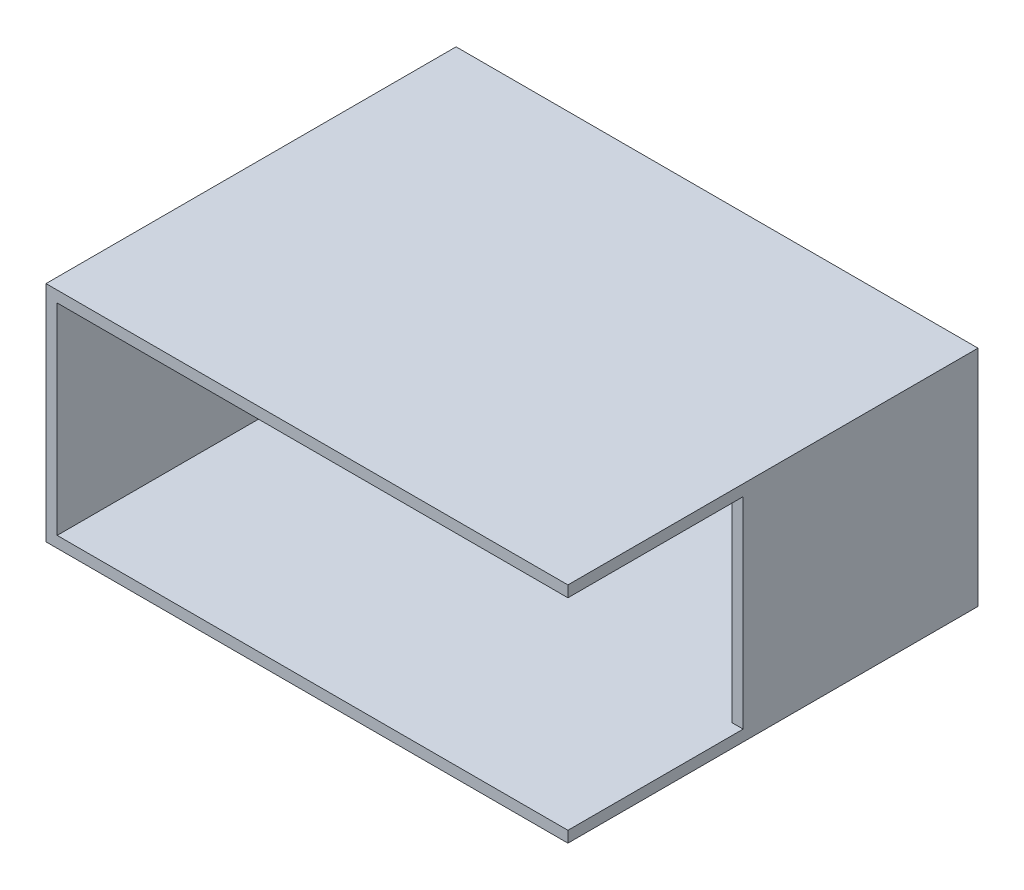
SolidWorks part; units mm, degrees
ref_plane "Front Plane" through (0, 0, 0) normal (1, 0, 0) x (0, 1, 0)
ref_plane "Top Plane" through (0, 0, 0) normal (0, 0, 1) x (0, 1, 0)
ref_plane "Right Plane" through (0, 0, 0) normal (0, 1, 0) x (-1, 0, 0)
sketch "Sketch1" plane through (0, 0, 0) normal (1, 0, 0) x (0, 1, 0)
  line L1 (0, 0) -> (76.2, 0)
  line L2 (0, 0) -> (0, 139.7)
  line L3 (0, 139.7) -> (76.2, 139.7)
  line L4 (76.2, 0) -> (76.2, 139.7)
  dimension "D1" = 139.7
  dimension "D2" = 76.2
extrude "Boss-Extrude1" add sketch "Sketch1" along normal blind 177.8
sketch "Sketch2" plane through (177.8, 0, 0) normal (1, 0, 0) x (0, 1, 0)
  line L0 (76.2, 139.7) -> (0, 139.7) construction
  line L1 (3.81, 139.7) -> (72.39, 139.7)
  line L2 (3.81, 139.7) -> (3.81, 3.81)
  line L3 (3.81, 3.81) -> (72.39, 3.81)
  line L4 (72.39, 139.7) -> (72.39, 3.81)
  line L5 (0, 139.7) -> (0, 0) construction
  line L6 (0, 0) -> (76.2, 0) construction
  line L7 (76.2, 0) -> (76.2, 139.7) construction
  dimension "D1" = 3.81
  dimension "D2" = 3.81
  dimension "D3" = 3.81
extrude "Cut-Extrude1" cut sketch "Sketch2" against normal blind 173.99
sketch "Sketch3" plane through (0, 0, 3.81) normal (0, 0, 1) x (1, 0, 0)
  line L0 (3.81, 3.81) -> (177.8, 3.81) construction
  line L1 (24.13, 29.21) -> (168.91, 29.21)
  line L2 (24.13, 29.21) -> (24.13, 46.99)
  line L3 (24.13, 46.99) -> (168.91, 46.99)
  line L4 (168.91, 29.21) -> (168.91, 46.99)
  line L6 (177.8, 3.81) -> (177.8, 72.39) construction
  line L8 (3.81, 72.39) -> (3.81, 3.81) construction
  dimension "D1" = 17.78
  dimension "D2" = 25.4
  dimension "D3" = 8.89
  dimension "D4" = 20.32
  dimension "D5" = 144.78
extrude "Cut-Extrude2" cut sketch "Sketch3" against normal blind 1.27
sketch "Sketch5" plane through (0, 0, 3.81) normal (0, 0, 1) x (1, 0, 0)
  line L0 (3.81, 3.81) -> (177.8, 3.81) construction
  line L1 (177.8, 72.39) -> (173.99, 72.39)
  line L2 (177.8, 72.39) -> (177.8, 3.81)
  line L3 (177.8, 3.81) -> (173.99, 3.81)
  line L4 (173.99, 72.39) -> (173.99, 3.81)
  dimension "D1" = 3.81
extrude "Boss-Extrude2" add sketch "Sketch5" along normal blind 76.2
